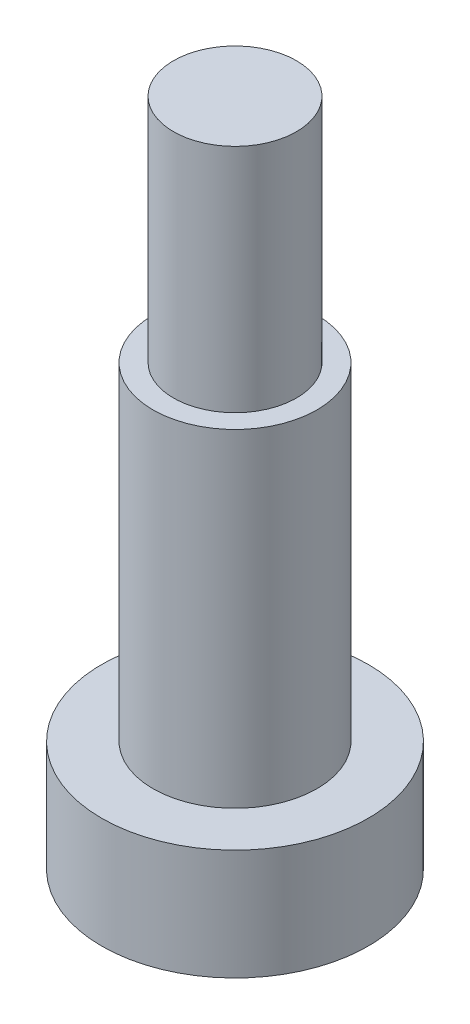
SolidWorks part; units mm, degrees
ref_plane "前视基准面" through (0, 0, 0) normal (0, 0, 1) x (1, 0, 0)
ref_plane "上视基准面" through (0, 0, 0) normal (0, 1, 0) x (1, 0, 0)
ref_plane "右视基准面" through (0, 0, 0) normal (1, 0, 0) x (0, 0, -1)
sketch "草图1" plane through (0, 0, 0) normal (0, 1, 0) x (1, 0, 0)
  circle A0 centre (0, 0) radius 6.5
  dimension "D1" = 13
extrude "凸台-拉伸1" add sketch "草图1" along normal blind 5.4
sketch "草图2" plane through (0, 5.4, 0) normal (0, 1, 0) x (1, 0, 0)
  circle A0 centre (0, 0) radius 4
  dimension "D1" = 8
extrude "凸台-拉伸2" add sketch "草图2" along normal blind 16
sketch "草图3" plane through (0, 21.4, 0) normal (0, 1, 0) x (1, 0, 0)
  circle A0 centre (0, 0) radius 3
  dimension "D1" = 6
extrude "凸台-拉伸3" add sketch "草图3" along normal blind 11.25
